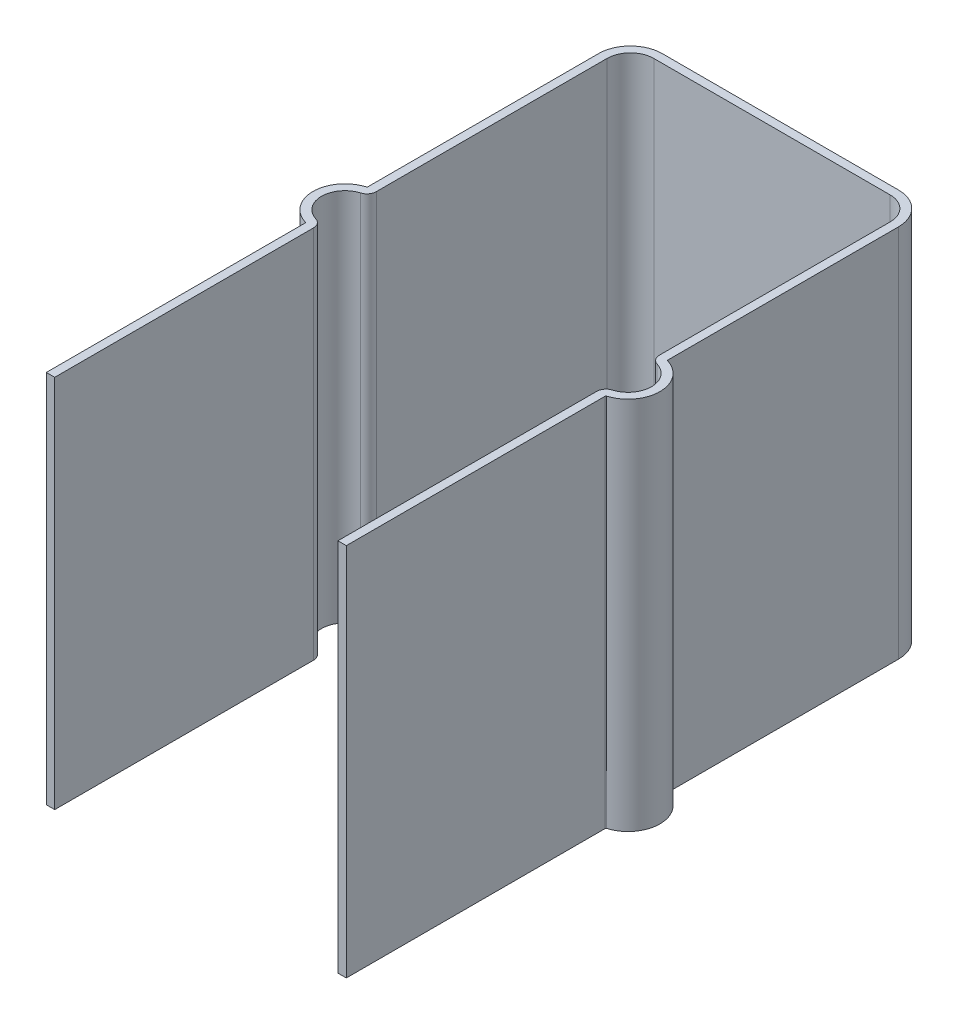
SolidWorks part; units mm, degrees
material "Alloy Steel"
ref_plane "Front Plane" through (0, 0, 0) normal (0, 0, 1) x (1, 0, 0)
ref_plane "Top Plane" through (0, 0, 0) normal (0, 1, 0) x (1, 0, 0)
ref_plane "Right Plane" through (0, 0, 0) normal (1, 0, 0) x (0, 0, -1)
sketch "Sketch1" plane through (0, 0, 0) normal (0, 1, 0) x (1, 0, 0)
  line L0 (-55, 0) -> (55, 0) construction
  line L1 (0, -55) -> (0, 55) construction
  line L2 (-3.025, 0.6708) -> (-3.025, 5.6)
  line L3 (-2.525, 6.1) -> (2.525, 6.1)
  line L4 (3.025, 5.6) -> (3.025, 0.6708)
  line L5 (-3.025, -0.6708) -> (-3.025, -6.2)
  line L6 (3.025, -0.6708) -> (3.025, -6.2)
  circle A0 centre (-3.025, 0) radius 0.5 construction
  circle A1 centre (3.025, 0) radius 0.5 construction
  arc A2 (-3.025, 5.6) -> (-2.525, 6.1) centre (-2.525, 5.6) cw
  arc A3 (2.525, 6.1) -> (3.025, 5.6) centre (2.525, 5.6) cw
  arc A4 (-3.1679, 0.4792) -> (-3.1679, -0.4792) centre (-3.025, 0) ccw
  arc A5 (3.1679, 0.4792) -> (3.1679, -0.4792) centre (3.025, 0) cw
  arc A6 (3.025, 0.6708) -> (3.1679, 0.4792) centre (3.225, 0.6708) ccw
  arc A7 (3.025, -0.6708) -> (3.1679, -0.4792) centre (3.225, -0.6708) cw
  arc A8 (-3.025, -0.6708) -> (-3.1679, -0.4792) centre (-3.225, -0.6708) ccw
  arc A9 (-3.025, 0.6708) -> (-3.1679, 0.4792) centre (-3.225, 0.6708) cw
  point P24 (3.025, 0.5)
  point P27 (3.025, -0.5)
  point P30 (-3.025, -0.5)
  point P33 (-3.025, 0.5)
  dimension "D1" = 1
  dimension "D5" = 0.5
  dimension "D8" = 0.2
  dimension "D2" = 6.05
  dimension "D3" = 3.025
  dimension "D4" = 12.3
  dimension "D6" = 6.1
  dimension "D7" = 6.2
extrude "Extrude-Thin1" add sketch "Sketch1" along normal blind 8 thin thin type one direction reverse wall 0.18
